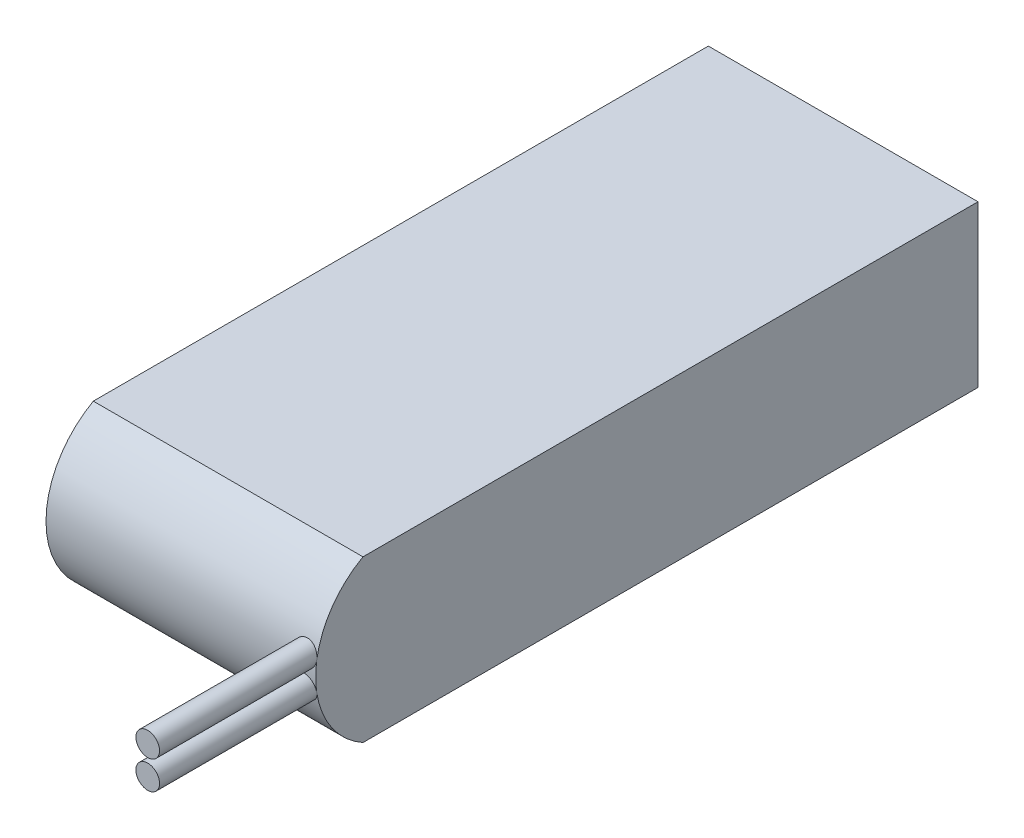
SolidWorks part; units mm, degrees
ref_plane "Plan de face" through (0, 0, 0) normal (0, 0, 1) x (1, 0, 0)
ref_plane "Plan de dessus" through (0, 0, 0) normal (0, 1, 0) x (1, 0, 0)
ref_plane "Plan de droite" through (0, 0, 0) normal (1, 0, 0) x (0, 0, -1)
sketch "Esquisse1" plane through (0, 0, 0) normal (0, 0, 1) x (1, 0, 0)
  line L1 (0, 0) -> (57, 0)
  line L2 (0, 0) -> (0, 34)
  line L3 (0, 34) -> (57, 34)
  line L4 (57, 0) -> (57, 34)
  dimension "D1" = 34
  dimension "D2" = 57
extrude "Boss.-Extru.1" add sketch "Esquisse1" along normal blind 130
sketch "Esquisse2" plane through (57, 0, 0) normal (1, 0, 0) x (0, 0, -1)
  line L0 (-130, 0) -> (-130, 34) construction
  line L1 (-130, 34) -> (-130, 0)
  arc A0 (-130, 34) -> (-130, 0) centre (-120.55, 17) ccw
  point P7 (-140, 17)
  dimension "D1" = 10
extrude "Boss.-Extru.2" add sketch "Esquisse2" against normal up to vertex (57 mm away) up to point (0, 34, 130)
sketch "Esquisse3" plane through (0, 0, 0) normal (0, 0, -1) x (-1, 0, 0)
  line L0 (-57, 0) -> (-57, 34) construction
  line L1 (-54.5, 20) -> (-54.5, 14) construction
  line L2 (-57, 17) -> (0, 17) construction
  line L3 (0, 34) -> (0, 0) construction
  circle A0 centre (-54.5, 20) radius 2.5
  circle A1 centre (-54.5, 14) radius 2.5
  point P9 (-54.5, 14)
  dimension "D1" = 5
  dimension "D2" = 3
  dimension "D3" = 3
extrude "Boss.-Extru.3" add sketch "Esquisse3" against normal blind 173
